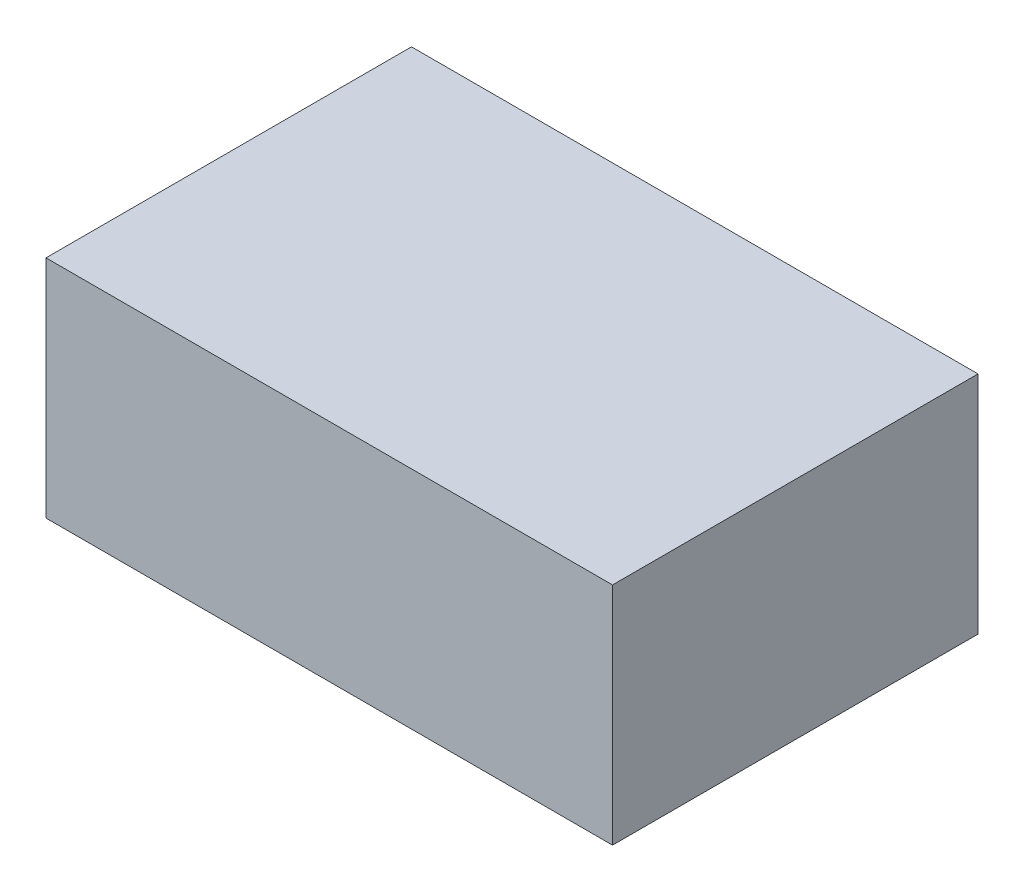
SolidWorks part; units mm, degrees
ref_plane "Front Plane" through (0, 0, 0) normal (0, 0, 1) x (1, 0, 0)
ref_plane "Top Plane" through (0, 0, 0) normal (0, 1, 0) x (1, 0, 0)
ref_plane "Right Plane" through (0, 0, 0) normal (1, 0, 0) x (0, 0, -1)
sketch "Sketch1" plane through (0, 0, 0) normal (0, 1, 0) x (1, 0, 0)
  line L1 (147.6375, -95.25) -> (-147.6375, -95.25)
  line L2 (147.6375, -95.25) -> (147.6375, 95.25)
  line L3 (147.6375, 95.25) -> (-147.6375, 95.25)
  line L4 (-147.6375, -95.25) -> (-147.6375, 95.25)
  line L5 (147.6375, -95.25) -> (-147.6375, 95.25) construction
  line L6 (147.6375, 95.25) -> (-147.6375, -95.25) construction
  point P0 (0, 0)
  dimension "D1" = 295.275
  dimension "D2" = 190.5
extrude "Boss-Extrude1" add sketch "Sketch1" along normal blind 117.475
